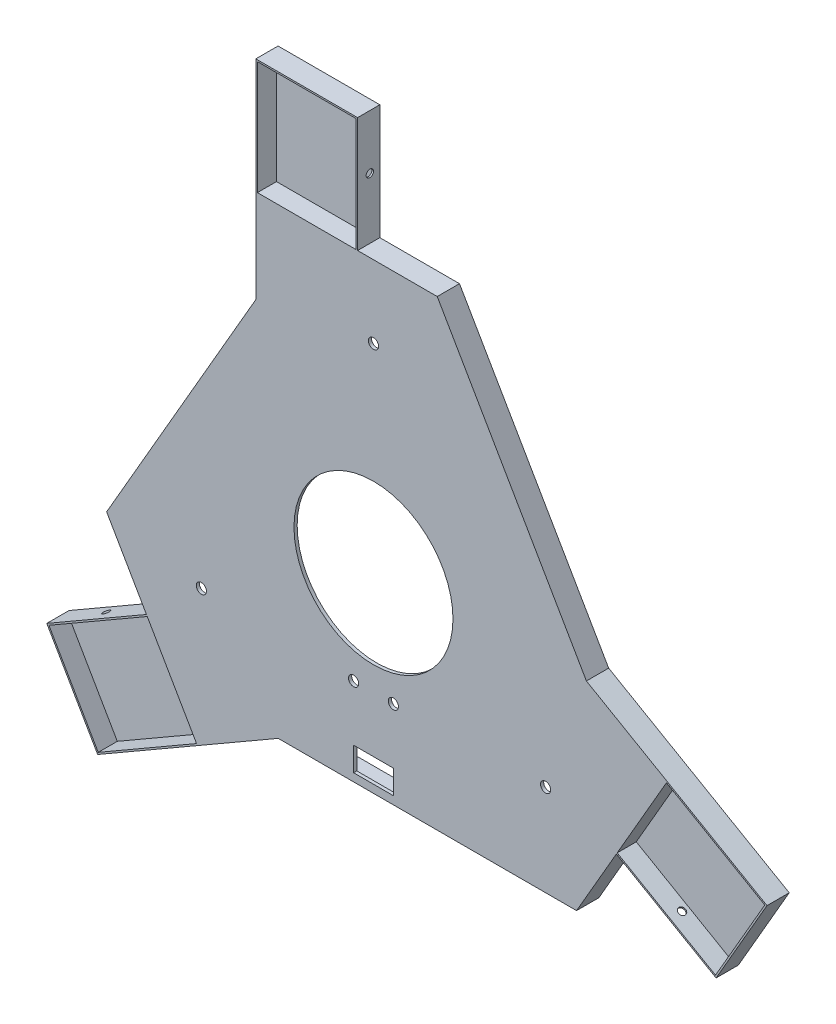
SolidWorks part; units mm, degrees
ref_plane "前视基准面" through (0, 0, 0) normal (0, 0, 1) x (1, 0, 0)
ref_plane "上视基准面" through (0, 0, 0) normal (0, 1, 0) x (1, 0, 0)
ref_plane "右视基准面" through (0, 0, 0) normal (1, 0, 0) x (0, 0, -1)
sketch "草图1" plane through (0, 0, 0) normal (0, 0, 1) x (1, 0, 0)
  circle A0 centre (0, 0) radius 255
  dimension "D1" = 510
extrude "拉伸1" add sketch "草图1" along normal blind 1
sketch "草图2" plane through (0, 0, 1) normal (0, 0, 1) x (1, 0, 0)
  line L0 (0, 0) -> (0, 49000) construction
  line L1 (-74, 244.0266) -> (-74, 111.9008)
  line L2 (-866.0254, -500) -> (0, 0) construction
  line L3 (866.0254, -500) -> (0, 0) construction
  line L5 (-148.775, -17.6132) -> (-167.8163, -50.5937)
  line L6 (133.909, 8.1355) -> (248.3333, -57.9274)
  line L7 (-174.3333, -186.0992) -> (-59.909, -120.0363)
  line L8 (59.134, 137.6495) -> (40.0927, 170.63)
  line L9 (-30, 150.1111) -> (30, 150.1111) construction
  line L10 (30, 150.1111) -> (145, -49.0748) construction
  line L11 (145, -49.0748) -> (115, -101.0363) construction
  line L12 (115, -101.0363) -> (-115, -101.0363) construction
  line L13 (-115, -101.0363) -> (-145, -49.0748) construction
  line L14 (-145, -49.0748) -> (-30, 150.1111) construction
  line L15 (-115, 2.8868) -> (-60, 98.1495) construction
  line L16 (-55, -101.0363) -> (55, -101.0363) construction
  line L17 (115, 2.8868) -> (60, 98.1495) construction
  line L18 (-215.6666, -136.0622) -> (-142.7699, -93.9753)
  line L19 (-142.7699, -93.9753) -> (-167.8163, -50.5937)
  line L20 (225.6666, -118.7417) -> (152.7699, -76.6547)
  line L21 (152.7699, -76.6547) -> (127.7236, -120.0363)
  line L22 (-10, 254.8038) -> (-10, 170.63)
  line L23 (-10, 170.63) -> (40.0927, 170.63)
  line L24 (-74, 111.9008) -> (-148.775, -17.6132)
  line L25 (59.134, 137.6495) -> (133.909, 8.1355)
  line L26 (-59.909, -120.0363) -> (89.641, -120.0363)
  line L27 (89.641, -120.0363) -> (127.7236, -120.0363)
  circle A0 centre (0, 0) radius 255 construction
  arc A1 (-74, 244.0266) -> (-215.6666, -136.0622) centre (0, 0) ccw
  arc A2 (248.3333, -57.9274) -> (-10, 254.8038) centre (0, 0) ccw
  arc A3 (-174.3333, -186.0992) -> (225.6666, -118.7417) centre (0, 0) ccw
  dimension "D6" = 74
  dimension "D1" = 74
  dimension "D3" = 170.63
  dimension "D4" = 74
  dimension "D7" = 230
  dimension "D8" = 60
  dimension "D9" = 230
  dimension "D10" = 60
  dimension "D11" = 60
  dimension "D12" = 230
  dimension "D13" = 30
  dimension "D14" = 30
  dimension "D15" = 10
  dimension "D16" = 10
  dimension "D17" = 10
  dimension "D18" = 170.63
  dimension "D19" = 19
  dimension "D20" = 170.63
  dimension "D21" = 19
  dimension "D22" = 19
extrude "切除-拉伸1" cut sketch "草图2" against normal through all
sketch "草图7" plane through (0, 0, 0) normal (0, 0, -1) x (-1, 0, 0)
  line L15 (-133.909, 8.1355) -> (-248.3333, -57.9274)
  line L17 (-225.6666, -118.7417) -> (-152.7699, -76.6547)
  line L18 (-152.7699, -76.6547) -> (-127.7236, -120.0363)
  line L19 (-127.7236, -120.0363) -> (59.909, -120.0363)
  line L20 (59.909, -120.0363) -> (174.3333, -186.0992)
  line L22 (215.6666, -136.0622) -> (142.7699, -93.9753)
  line L23 (142.7699, -93.9753) -> (167.8163, -50.5937)
  line L24 (167.8163, -50.5937) -> (74, 111.9008)
  line L25 (74, 111.9008) -> (74, 244.0266)
  line L27 (10, 254.8038) -> (10, 170.63)
  line L28 (10, 170.63) -> (-40.0927, 170.63)
  line L29 (-40.0927, 170.63) -> (-133.909, 8.1355)
  line L30 (-133.909, 8.1355) -> (-248.3333, -57.9274)
  line L32 (-225.6666, -118.7417) -> (-152.7699, -76.6547)
  line L33 (-152.7699, -76.6547) -> (-127.7236, -120.0363)
  line L34 (-127.7236, -120.0363) -> (59.909, -120.0363)
  line L35 (59.909, -120.0363) -> (174.3333, -186.0992)
  line L37 (215.6666, -136.0622) -> (142.7699, -93.9753)
  line L38 (142.7699, -93.9753) -> (167.8163, -50.5937)
  line L39 (167.8163, -50.5937) -> (74, 111.9008)
  line L40 (74, 111.9008) -> (74, 244.0266)
  line L42 (10, 254.8038) -> (10, 170.63)
  line L43 (10, 170.63) -> (-40.0927, 170.63)
  line L44 (-40.0927, 170.63) -> (-133.909, 8.1355)
  arc A3 (174.3333, -186.0992) -> (215.6666, -136.0622) centre (0, 0) ccw
  arc A4 (174.3333, -186.0992) -> (215.6666, -136.0622) centre (0, 0) ccw
  arc A5 (74, 244.0266) -> (10, 254.8038) centre (0, 0) ccw
  arc A6 (74, 244.0266) -> (10, 254.8038) centre (0, 0) ccw
  arc A7 (-248.3333, -57.9274) -> (-225.6666, -118.7417) centre (0, 0) ccw
  arc A8 (-248.3333, -57.9274) -> (-225.6666, -118.7417) centre (0, 0) ccw
  dimension "D1" = 0
extrude "拉伸3" add sketch "草图7" along normal blind 13
sketch "草图8" plane through (0, 0, -13) normal (0, 0, -1) x (-1, 0, 0)
  line L5 (-39.5154, 169.63) -> (-133.1769, 7.4034)
  line L7 (-133.1769, 7.4034) -> (-183.4039, -21.5951)
  line L9 (-151.9039, -76.1547) -> (-183.4039, -21.5951)
  line L10 (-151.9039, -76.1547) -> (-127.1462, -119.0363)
  line L13 (-127.1462, -119.0363) -> (60.1769, -119.0363)
  line L14 (60.1769, -119.0363) -> (110.4039, -148.0349)
  line L18 (141.9039, -93.4753) -> (110.4039, -148.0349)
  line L19 (141.9039, -93.4753) -> (166.6616, -50.5937)
  line L20 (166.6616, -50.5937) -> (73, 111.6329)
  line L21 (73, 111.6329) -> (73, 169.63)
  line L22 (10, 169.63) -> (73, 169.63)
  line L23 (10, 169.63) -> (-39.5154, 169.63)
extrude "切除-拉伸6" cut sketch "草图8" against normal blind 12
sketch "草图9" plane through (0, 0, -1) normal (0, 0, -1) x (-1, 0, 0)
  circle A0 centre (0, 0) radius 50
  dimension "D1" = 100
extrude "切除-拉伸7" cut sketch "草图9" against normal blind 14
sketch "草图10" plane through (0, 0, 1) normal (0, 0, 1) x (1, 0, 0)
  line L0 (225.6666, -118.7417) -> (152.7699, -76.6547) construction
  line L1 (133.909, 8.1355) -> (248.3333, -57.9274) construction
  line L2 (225.6666, -118.7417) -> (215.4672, -112.8531)
  line L3 (-74, 243.0266) -> (-10, 243.0266)
  line L4 (-215.6666, -136.0622) -> (-142.7699, -93.9753) construction
  line L5 (-59.909, -120.0363) -> (-174.3333, -186.0992) construction
  line L6 (-215.6666, -136.0622) -> (-205.4672, -130.1736)
  line L7 (-173.4672, -185.5992) -> (-174.3333, -186.0992)
  line L9 (-173.4672, -185.5992) -> (-205.4672, -130.1736)
  line L11 (247.4672, -57.4274) -> (248.3333, -57.9274)
  line L13 (247.4672, -57.4274) -> (215.4672, -112.8531)
  line L21 (-174.3333, -186.0992) -> (-59.909, -120.0363)
  line L22 (-59.909, -120.0363) -> (127.7236, -120.0363)
  line L23 (127.7236, -120.0363) -> (152.7699, -76.6547)
  line L24 (152.7699, -76.6547) -> (225.6666, -118.7417)
  line L25 (248.3333, -57.9274) -> (133.909, 8.1355)
  line L26 (133.909, 8.1355) -> (40.0927, 170.63)
  line L27 (40.0927, 170.63) -> (-10, 170.63)
  line L28 (-10, 170.63) -> (-10, 254.8038)
  line L29 (-74, 244.0266) -> (-74, 111.9008)
  line L30 (-74, 111.9008) -> (-167.8163, -50.5937)
  line L31 (-167.8163, -50.5937) -> (-142.7699, -93.9753)
  line L32 (-142.7699, -93.9753) -> (-215.6666, -136.0622)
  line L40 (-10, 243.0266) -> (-10, 254.8038)
  line L41 (-74, 244.0266) -> (-74, 243.0266)
  arc A3 (-215.6666, -136.0622) -> (-174.3333, -186.0992) centre (0, 0) ccw construction
  arc A4 (-215.6666, -136.0622) -> (-174.3333, -186.0992) centre (0, 0) ccw
  arc A5 (225.6666, -118.7417) -> (248.3333, -57.9274) centre (0, 0) ccw construction
  arc A6 (225.6666, -118.7417) -> (248.3333, -57.9274) centre (0, 0) ccw
  arc A9 (225.6666, -118.7417) -> (248.3333, -57.9274) centre (0, 0) ccw
  arc A10 (-10, 254.8038) -> (-74, 244.0266) centre (0, 0) ccw
  arc A11 (-215.6666, -136.0622) -> (-174.3333, -186.0992) centre (0, 0) ccw
  arc A13 (-10, 254.8038) -> (-74, 244.0266) centre (0, 0) ccw
  dimension "D1" = 0
extrude "切除-拉伸8" cut sketch "草图10" against normal blind 24
sketch "草图11" plane through (0, 0, 1) normal (0, 0, 1) x (1, 0, 0)
  line L0 (-11, 170.6696) -> (-73, 170.6696)
  line L1 (-73, 242.0266) -> (-73, 171.63)
  line L2 (-11, 171.63) -> (-11, 242.0266)
  line L6 (-73, 170.6696) -> (-73, 171.63)
  line L7 (-11, 171.63) -> (-11, 170.6696)
  line L11 (153.2699, -75.7887) -> (184.2699, -22.0951)
  line L14 (246.1012, -57.7935) -> (215.1012, -111.487)
  line L15 (-173.1012, -184.2332) -> (-204.1012, -130.5396)
  line L16 (215.1012, -111.487) -> (153.2699, -75.7887)
  line L18 (184.2699, -22.0951) -> (246.1012, -57.7935)
  line L19 (-142.2699, -94.8413) -> (-111.2699, -148.5349)
  line L20 (-111.2699, -148.5349) -> (-173.1012, -184.2332)
  line L22 (-204.1012, -130.5396) -> (-142.2699, -94.8413)
  line L23 (-73, 242.0266) -> (-11, 242.0266)
extrude "切除-拉伸9" cut sketch "草图11" against normal blind 12
sketch "草图12" plane through (0, 0, -1) normal (0, 0, -1) x (-1, 0, 0)
  line L0 (0, -1000) -> (0, 49000) construction
  line L1 (-987.5, -65) -> (49012.5, -65) construction
  circle A0 centre (-12.5, -65) radius 3.2
  circle A1 centre (12.5, -65) radius 3.2
  dimension "D1" = 6.4
  dimension "D2" = 6.4
  dimension "D3" = 25
  dimension "D4" = 12.5
  dimension "D5" = 65
extrude "切除-拉伸10" cut sketch "草图12" against normal blind 10
sketch "草图13" plane through (0, 0, -1) normal (0, 0, -1) x (-1, 0, 0)
  line L0 (0, -1000) -> (0, 49000) construction
  line L1 (-866.0254, -500) -> (42435.2448, 24500) construction
  line L2 (866.0254, -500) -> (-42435.2448, 24500) construction
  circle A0 centre (0, 0) radius 125 construction
  circle A1 centre (0, 125) radius 3.2
  circle A2 centre (108.2532, -62.5) radius 3.2
  circle A3 centre (-108.2532, -62.5) radius 3.2
  dimension "D1" = 250
  dimension "D2" = 6.4
extrude "切除-拉伸11" cut sketch "草图13" against normal blind 10
sketch "草图14" plane through (5, -8.6603, 0) normal (-0.5, 0.866, 0) x (-0.866, -0.5, 0)
  circle A0 centre (208.8328, -6.6957) radius 2.25
  dimension "D1" = 4.5
sketch "草图15" plane through (5, 8.6603, 0) normal (-0.5, -0.866, 0) x (0.866, -0.5, 0)
  circle A0 centre (208.8328, -6.6957) radius 2.25
  dimension "D1" = 4.5
sketch "草图16" plane through (-10, 0, 0) normal (1, 0, 0) x (0, 0, -1)
  circle A0 centre (6.6957, 208.8328) radius 2.3
  dimension "D1" = 4.6
extrude "切除-拉伸12" cut sketch "草图14" against normal blind 10
extrude "切除-拉伸13" cut sketch "草图16" against normal blind 10
extrude "切除-拉伸14" cut sketch "草图15" against normal blind 10
sketch "草图17" plane through (0, 0, -1) normal (0, 0, -1) x (-1, 0, 0)
  line L0 (0, -1000) -> (0, 49000) construction
  line L1 (-127.7236, -120.0363) -> (59.909, -120.0363) construction
  line L2 (-12.5, -100.0363) -> (12.5, -100.0363)
  line L3 (-12.5, -100.0363) -> (-12.5, -115.0363)
  line L4 (-12.5, -115.0363) -> (12.5, -115.0363)
  line L5 (12.5, -100.0363) -> (12.5, -115.0363)
  dimension "D1" = 15
  dimension "D2" = 25
  dimension "D3" = 12.5
  dimension "D4" = 20
extrude "切除-拉伸15" cut sketch "草图17" against normal blind 4.5
